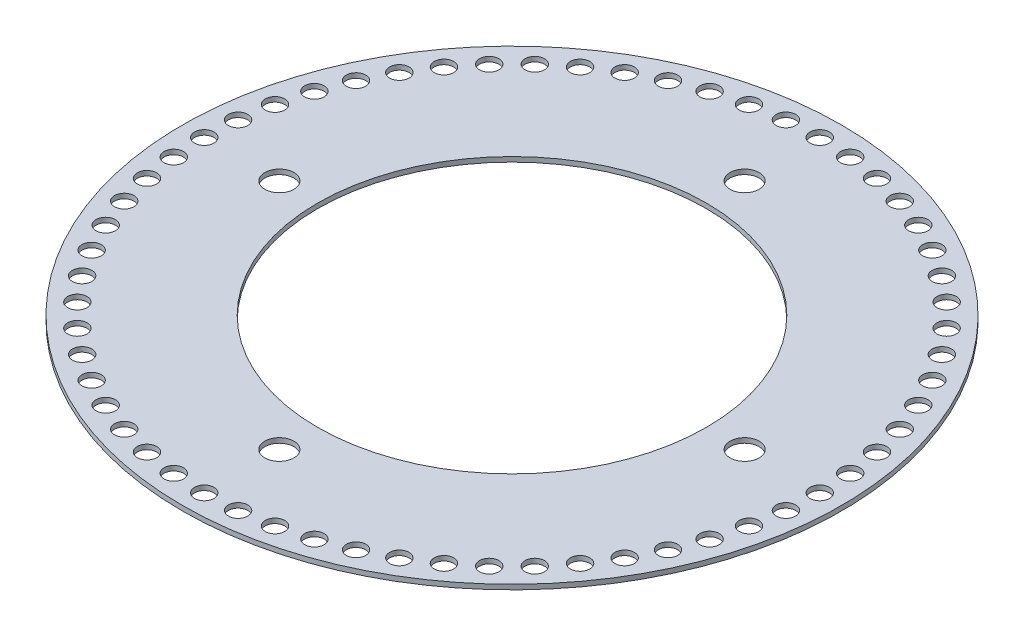
SolidWorks part; units mm, degrees
ref_plane "Front Plane" through (0, 0, 0) normal (0, 0, 1) x (1, 0, 0)
ref_plane "Top Plane" through (0, 0, 0) normal (0, 1, 0) x (1, 0, 0)
ref_plane "Right Plane" through (0, 0, 0) normal (1, 0, 0) x (0, 0, -1)
sketch "Sketch1" plane through (0, 0, 0) normal (0, 1, 0) x (1, 0, 0)
  circle A0 centre (0, 0) radius 34
  circle A1 centre (0, 0) radius 20.05
extrude "Boss-Extrude1" add sketch "Sketch1" along normal blind 0.5
sketch "Sketch2" plane through (0, 0.5, 0) normal (0, 1, 0) x (1, 0, 0)
  line L0 (0, 34) -> (16.9438, 34) construction
  circle A1 centre (0, 31.75) radius 1
  circle A2 centre (3.3188, 31.5761) radius 1
  circle A3 centre (6.6012, 31.0562) radius 1
  circle A4 centre (9.8113, 30.196) radius 1
  circle A5 centre (12.9139, 29.0051) radius 1
  circle A6 centre (15.875, 27.4963) radius 1
  circle A7 centre (18.6622, 25.6863) radius 1
  circle A8 centre (21.2449, 23.5948) radius 1
  circle A9 centre (23.5948, 21.2449) radius 1
  circle A10 centre (25.6863, 18.6622) radius 1
  circle A11 centre (27.4963, 15.875) radius 1
  circle A12 centre (29.0051, 12.9139) radius 1
  circle A13 centre (30.196, 9.8113) radius 1
  circle A14 centre (31.0562, 6.6012) radius 1
  circle A15 centre (31.5761, 3.3188) radius 1
  circle A16 centre (31.75, 0) radius 1
  circle A17 centre (31.5761, -3.3188) radius 1
  circle A18 centre (31.0562, -6.6012) radius 1
  circle A19 centre (30.196, -9.8113) radius 1
  circle A20 centre (29.0051, -12.9139) radius 1
  circle A21 centre (27.4963, -15.875) radius 1
  circle A22 centre (25.6863, -18.6622) radius 1
  circle A23 centre (23.5948, -21.2449) radius 1
  circle A24 centre (21.2449, -23.5948) radius 1
  circle A25 centre (18.6622, -25.6863) radius 1
  circle A26 centre (15.875, -27.4963) radius 1
  circle A27 centre (12.9139, -29.0051) radius 1
  circle A28 centre (9.8113, -30.196) radius 1
  circle A29 centre (6.6012, -31.0562) radius 1
  circle A30 centre (3.3188, -31.5761) radius 1
  circle A31 centre (0, -31.75) radius 1
  circle A32 centre (-3.3188, -31.5761) radius 1
  circle A33 centre (-6.6012, -31.0562) radius 1
  circle A34 centre (-9.8113, -30.196) radius 1
  circle A35 centre (-12.9139, -29.0051) radius 1
  circle A36 centre (-15.875, -27.4963) radius 1
  circle A37 centre (-18.6622, -25.6863) radius 1
  circle A38 centre (-21.2449, -23.5948) radius 1
  circle A39 centre (-23.5948, -21.2449) radius 1
  circle A40 centre (-25.6863, -18.6622) radius 1
  circle A41 centre (-27.4963, -15.875) radius 1
  circle A42 centre (-29.0051, -12.9139) radius 1
  circle A43 centre (-30.196, -9.8113) radius 1
  circle A44 centre (-31.0562, -6.6012) radius 1
  circle A45 centre (-31.5761, -3.3188) radius 1
  circle A46 centre (-31.75, 0) radius 1
  circle A47 centre (-31.5761, 3.3188) radius 1
  circle A48 centre (-31.0562, 6.6012) radius 1
  circle A49 centre (-30.196, 9.8113) radius 1
  circle A50 centre (-29.0051, 12.9139) radius 1
  circle A51 centre (-27.4963, 15.875) radius 1
  circle A52 centre (-25.6863, 18.6622) radius 1
  circle A53 centre (-23.5948, 21.2449) radius 1
  circle A54 centre (-21.2449, 23.5948) radius 1
  circle A55 centre (-18.6622, 25.6863) radius 1
  circle A56 centre (-15.875, 27.4963) radius 1
  circle A57 centre (-12.9139, 29.0051) radius 1
  circle A58 centre (-9.8113, 30.196) radius 1
  circle A59 centre (-6.6012, 31.0562) radius 1
  circle A60 centre (-3.3188, 31.5761) radius 1
  point P124 (0, 0)
  dimension "D1" = 2.25
  dimension "D2" = 60
extrude "Cut-Extrude1" cut sketch "Sketch2" against normal through all
sketch "Sketch3" plane through (0, 0.5, 0) normal (0, 1, 0) x (1, 0, 0)
  circle A0 centre (0, 24) radius 1.5
  circle A1 centre (24, 0) radius 1.5
  circle A2 centre (0, -24) radius 1.5
  circle A3 centre (-24, 0) radius 1.5
  circle A4 centre (0, 0) radius 26.5 construction
  point P11 (0, 0)
  dimension "D1" = 24
extrude "Cut-Extrude2" cut sketch "Sketch3" against normal blind 10
